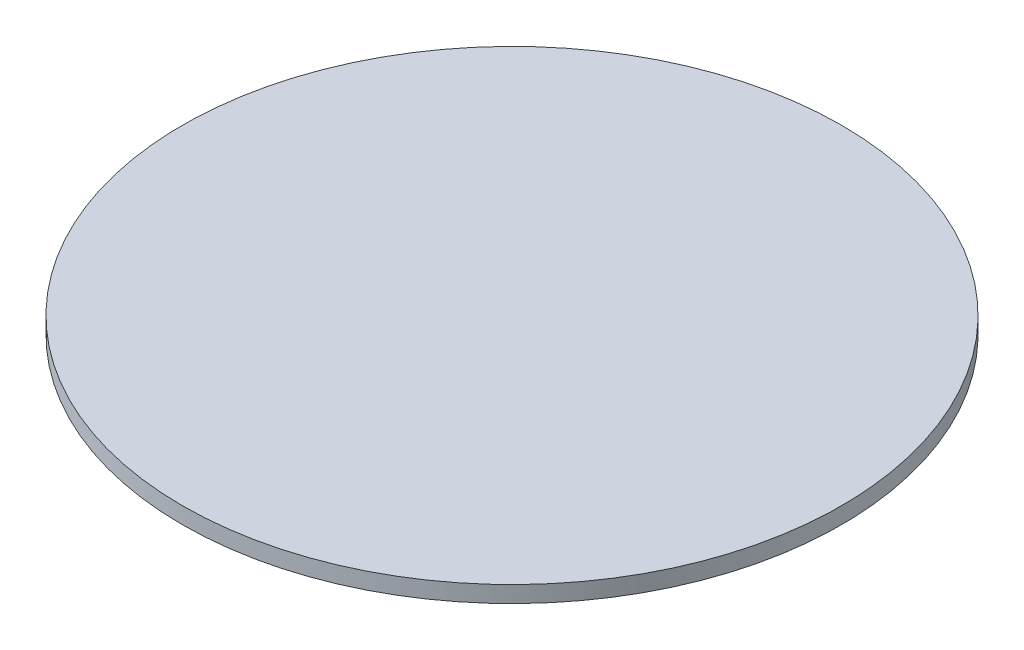
SolidWorks part; units mm, degrees
ref_plane "前视基准面" through (0, 0, 0) normal (0, 0, 1) x (1, 0, 0)
ref_plane "上视基准面" through (0, 0, 0) normal (0, 1, 0) x (1, 0, 0)
ref_plane "右视基准面" through (0, 0, 0) normal (1, 0, 0) x (0, 0, -1)
other "Configuration Table"
sketch "草图1" plane through (0, 0, 0) normal (0, 1, 0) x (1, 0, 0)
  circle A0 centre (0, 0) radius 60
  dimension "D1" = 120
extrude "凸台-拉伸1" add sketch "草图1" along normal blind 3
